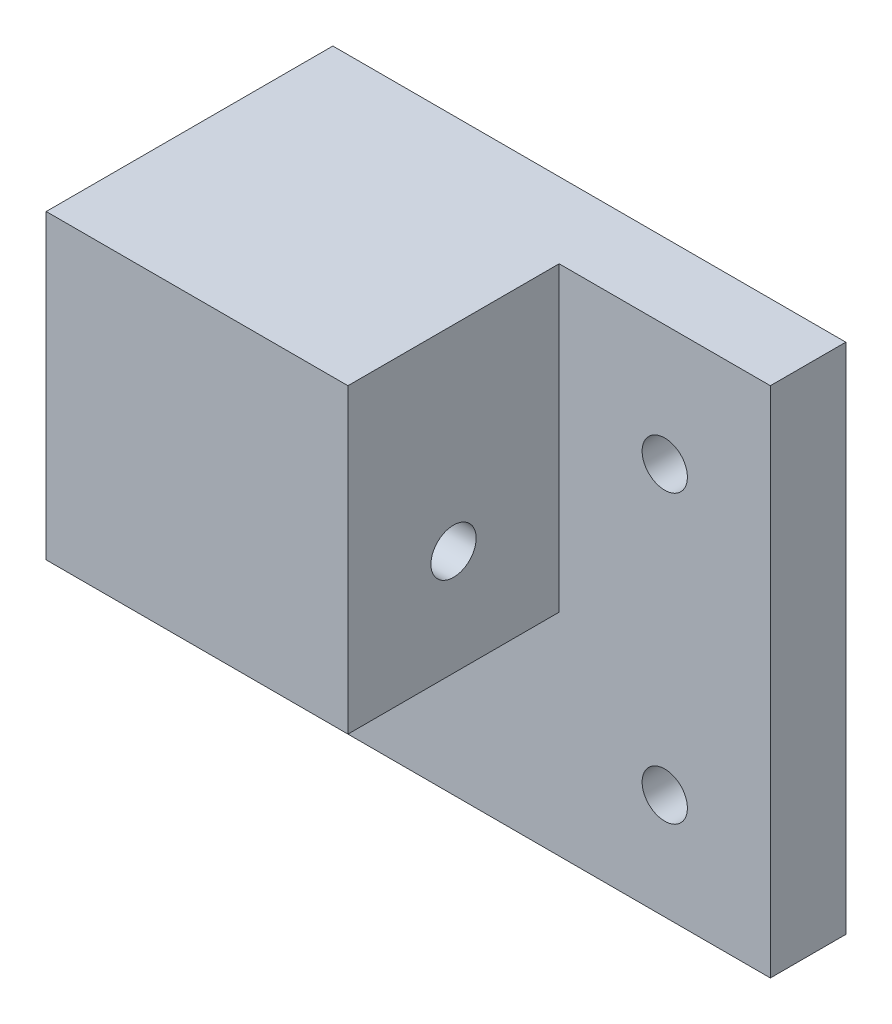
SolidWorks part; units mm, degrees
ref_plane "Ön Düzlem" through (0, 0, 0) normal (0, 0, 1) x (1, 0, 0)
ref_plane "Üst Düzlem" through (0, 0, 0) normal (0, 1, 0) x (1, 0, 0)
ref_plane "Sağ Düzlem" through (0, 0, 0) normal (1, 0, 0) x (0, 0, -1)
sketch "Çizim1" plane through (0, 0, 0) normal (0, 0, 1) x (1, 0, 0)
  line L1 (0, 0) -> (-68, 0)
  line L2 (0, 0) -> (0, -68)
  line L3 (0, -68) -> (-68, -68)
  line L4 (-68, 0) -> (-68, -68)
  dimension "D1" = 68
  dimension "D2" = 68
extrude "Yükseklik-Ekstrüzyon1" add sketch "Çizim1" along normal blind 10
sketch "Çizim2" plane through (0, 0, 10) normal (0, 0, 1) x (1, 0, 0)
  line L0 (0, -68) -> (0, 0) construction
  line L1 (-68, 0) -> (-28, 0)
  line L2 (-68, 0) -> (-68, -40)
  line L3 (-68, -40) -> (-28, -40)
  line L4 (-28, 0) -> (-28, -40)
  line L5 (-68, -68) -> (0, -68) construction
  dimension "D1" = 28
  dimension "D2" = 28
extrude "Yükseklik-Ekstrüzyon2" add sketch "Çizim2" along normal blind 28
sketch "Çizim3" plane through (0, -40, 0) normal (0, -1, 0) x (1, 0, 0)
  line L0 (0, 10) -> (0, 0) construction
  line L4 (-48, 38) -> (-48, 10) construction
  line L5 (-68, 38) -> (-28, 38) construction
  line L6 (-68, 10) -> (-28, 10) construction
  circle A0 centre (-42, 24) radius 3
  point P3 (-48, 24)
  dimension "D1" = 6
  dimension "D2" = 42
extrude "Kes-Ekstrüzyon1" cut sketch "Çizim3" against normal blind 20
sketch "Çizim4" plane through (-28, 0, 0) normal (1, 0, 0) x (0, 0, -1)
  line L0 (-10, -68) -> (0, -68) construction
  line L5 (-38, -20) -> (-10, -20) construction
  line L6 (-38, -40) -> (-38, 0) construction
  line L7 (-10, -40) -> (-10, 0) construction
  circle A0 centre (-24, -26) radius 3
  point P3 (-24, -20)
  dimension "D1" = 6
  dimension "D2" = 42
extrude "Kes-Ekstrüzyon2" cut sketch "Çizim4" against normal blind 20
sketch "Çizim5" plane through (0, 0, 10) normal (0, 0, 1) x (1, 0, 0)
  line L0 (0, -68) -> (0, 0) construction
  line L1 (-68, -68) -> (0, -68) construction
  line L2 (0, -68) -> (0, 0) construction
  circle A0 centre (-14, -54) radius 3
  circle A1 centre (-14, -16) radius 3
  circle A2 centre (-52, -54) radius 3
  dimension "D3" = 6
  dimension "D1" = 14
  dimension "D2" = 14
  dimension "D4" = 52
  dimension "D5" = 52
extrude "Kes-Ekstrüzyon3" cut sketch "Çizim5" against normal through all
